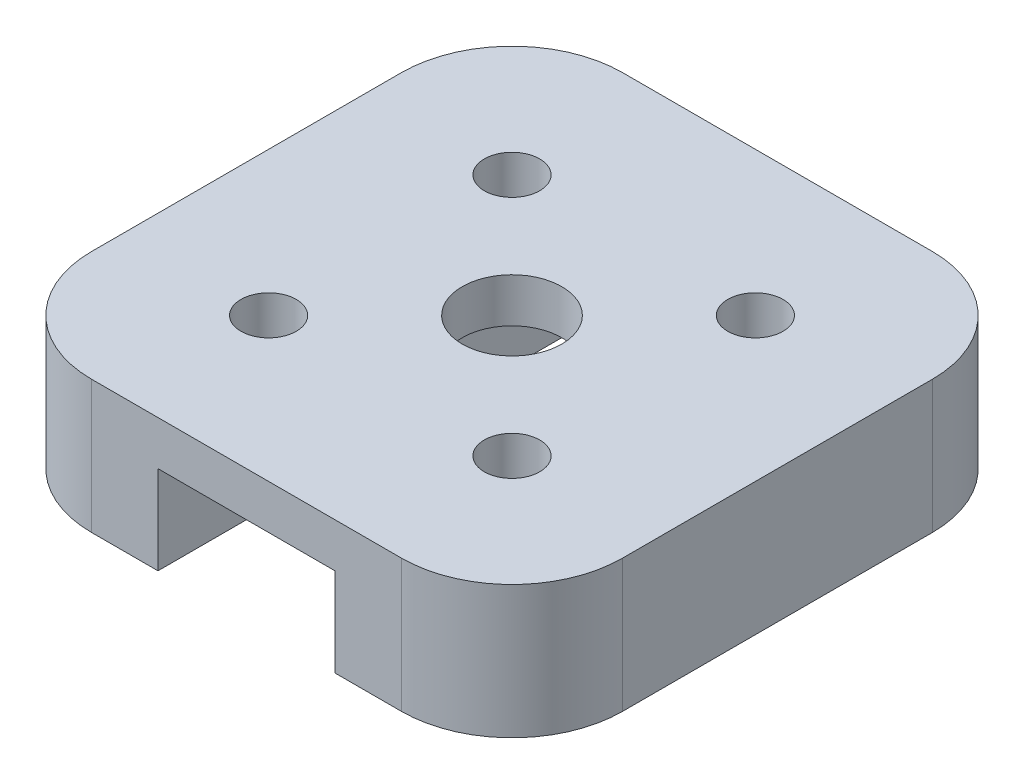
SolidWorks part; units mm, degrees
ref_plane "Front Plane" through (0, 0, 0) normal (0, 0, 1) x (1, 0, 0)
ref_plane "Top Plane" through (0, 0, 0) normal (0, 1, 0) x (1, 0, 0)
ref_plane "Right Plane" through (0, 0, 0) normal (1, 0, 0) x (0, 0, -1)
sketch "Sketch1" plane through (0, 0, 0) normal (0, 1, 0) x (1, 0, 0)
  line L1 (-7, 12) -> (7, 12)
  line L2 (-12, 7) -> (-12, -7)
  line L3 (-7, -12) -> (7, -12)
  line L4 (12, 7) -> (12, -7)
  arc A0 (-12, -7) -> (-7, -12) centre (-7, -7) ccw
  arc A1 (7, -12) -> (12, -7) centre (7, -7) ccw
  arc A2 (7, 12) -> (12, 7) centre (7, 7) cw
  arc A3 (-7, 12) -> (-12, 7) centre (-7, 7) ccw
  circle A4 centre (-5.5, 5.5) radius 1.25
  circle A5 centre (5.5, 5.5) radius 1.25
  circle A6 centre (5.5, -5.5) radius 1.25
  circle A7 centre (-5.5, -5.5) radius 1.25
  circle A8 centre (0, 0) radius 2.25
  dimension "D5" = 5
  dimension "D6" = 2.5
  dimension "D7" = 2.5
  dimension "D8" = 2.5
  dimension "D9" = 2.5
  dimension "D10" = 11
  dimension "D11" = 11
  dimension "D12" = 11
  dimension "D13" = 5.5
  dimension "D18" = 4.5
  dimension "D14" = 5.5
  dimension "D1" = 24
  dimension "D2" = 24
  dimension "D3" = 12
  dimension "D4" = 12
extrude "Boss-Extrude1" add sketch "Sketch1" along normal blind 6
sketch "Sketch2" plane through (0, 0, 12) normal (0, 0, 1) x (1, 0, 0)
  line L0 (-7, 0) -> (7, 0) construction
  line L1 (-4, 0) -> (4, 0)
  line L2 (-4, 0) -> (-4, 4)
  line L3 (-4, 4) -> (4, 4)
  line L4 (4, 0) -> (4, 4)
  dimension "D1" = 8
  dimension "D2" = 4
extrude "Cut-Extrude1" cut sketch "Sketch2" against normal through all both and the other way through all
